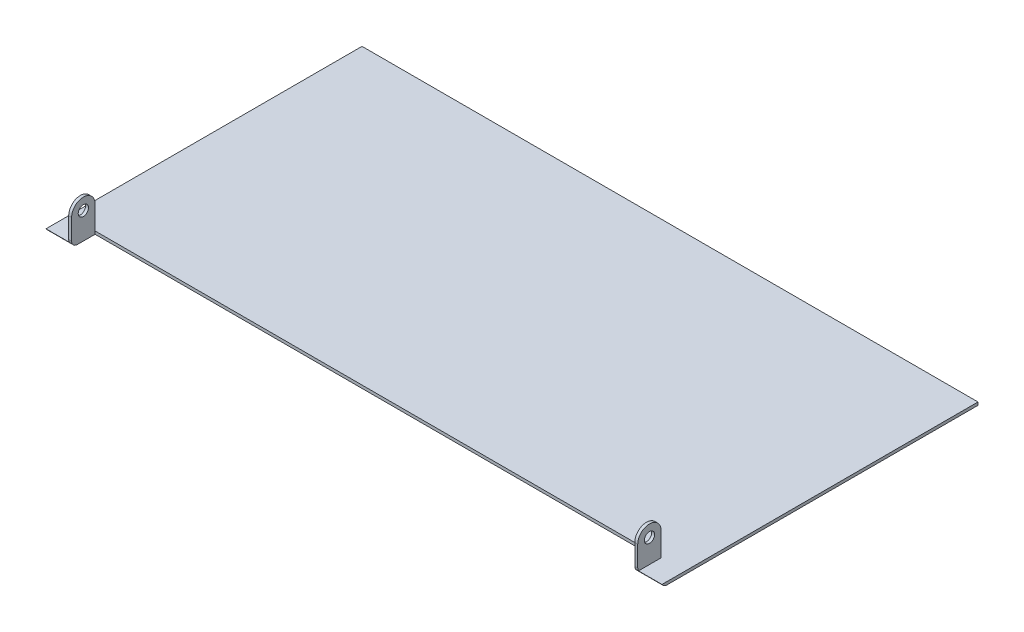
SolidWorks part; units mm, degrees
ref_plane "Front Plane" through (0, 0, 0) normal (0, 0, 1) x (1, 0, 0)
ref_plane "Top Plane" through (0, 0, 0) normal (0, 1, 0) x (1, 0, 0)
ref_plane "Right Plane" through (0, 0, 0) normal (1, 0, 0) x (0, 0, -1)
sketch "Sketch1" plane through (0, 0, 0) normal (0, 1, 0) x (1, 0, 0)
  line L1 (97, -50) -> (-97, -50)
  line L2 (97, -50) -> (97, 50)
  line L3 (97, 50) -> (-97, 50)
  line L4 (-97, -50) -> (-97, 50)
  line L5 (97, -50) -> (-97, 50) construction
  line L6 (97, 50) -> (-97, -50) construction
  point P0 (0, 0)
  dimension "D1" = 194
  dimension "D2" = 100
extrude "Boss-Extrude1" add sketch "Sketch1" along normal blind 1
sketch "Sketch2" plane through (-97, 0, 0) normal (-1, 0, 0) x (0, 0, 1)
  line L0 (58, 0) -> (58, 9)
  line L1 (50, 0) -> (50, 9)
  line L3 (58, 0) -> (50, 0)
  line L4 (-50, 0) -> (50, 0) construction
  arc A0 (50, 9) -> (58, 9) centre (54, 9) cw
  circle A1 centre (54, 9) radius 1.75
  dimension "D3" = 3.5
  dimension "D1" = 9
  dimension "D2" = 8
extrude "Boss-Extrude2" add sketch "Sketch2" against normal blind 1
sketch "Sketch3" plane through (0, 1, 0) normal (0, 1, 0) x (1, 0, 0)
  line L0 (0, 50) -> (0, -50) construction
  line L1 (97, 50) -> (-97, 50) construction
  line L2 (-96, -50) -> (97, -50) construction
ref_plane "Plane2" through (0, 0, 0) normal (-1, 0, 0) x (0, 0, 1)
mirror "Mirror1" about plane through (0, 0, 0) normal (-1, 0, 0) of "Boss-Extrude2"
sketch "Sketch4" plane through (-97, 0, 0) normal (-1, 0, 0) x (0, 0, 1)
  line L0 (-50, 0) -> (58, 0) construction
  line L3 (58, 0) -> (58, 9) construction
  line L4 (51, 0) -> (58, 0)
  line L5 (58, 0) -> (58, 4.5)
  spline S0 degree 3 poles (51, 0) (54.7889, 0.1908) (57.4925, 1.0174) (58, 4.5) knots 0 0 0 0 1 1 1 1
  dimension "D1" = 7
sketch "Sketch5" plane through (0, 1, 0) normal (0, 1, 0) x (1, 0, 0)
  line L1 (-97, 50) -> (-105, 50)
  line L2 (-97, 50) -> (-97, -58)
  line L3 (-97, -58) -> (-105, -58)
  line L4 (-105, 50) -> (-105, -58)
  line L5 (97, 50) -> (105, 50)
  line L6 (97, 50) -> (97, -58)
  line L7 (97, -58) -> (105, -58)
  line L8 (105, 50) -> (105, -58)
  dimension "D1" = 8
extrude "Boss-Extrude3" add sketch "Sketch5" against normal blind 1
sketch "Sketch6" plane through (-105, 0, 0) normal (-1, 0, 0) x (0, 0, 1)
  line L0 (58, 0) -> (56, 0)
  line L1 (51, 0) -> (58, 0) construction
  line L2 (58, 0) -> (58, 2)
  line L3 (58, 0) -> (58, 4.5) construction
  arc A0 (56, 0) -> (58, 2) centre (56, 2) ccw
  dimension "D1" = 2
extrude "Cut-Extrude3" cut sketch "Sketch6" against normal through all
